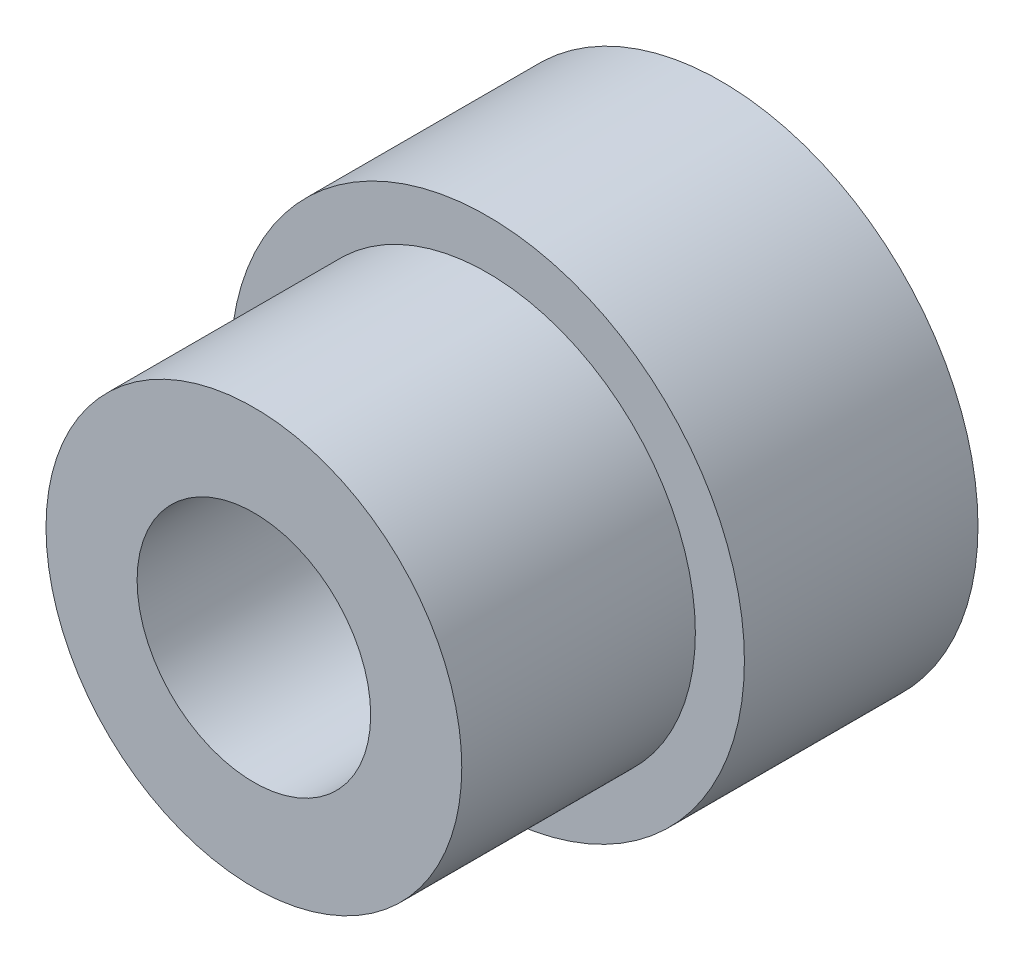
SolidWorks part; units mm, degrees
ref_plane "前视基准面" through (0, 0, 0) normal (0, 0, 1) x (1, 0, 0)
ref_plane "上视基准面" through (0, 0, 0) normal (0, 1, 0) x (1, 0, 0)
ref_plane "右视基准面" through (0, 0, 0) normal (1, 0, 0) x (0, 0, -1)
sketch "草图1" plane through (0, 0, 0) normal (0, 0, 1) x (1, 0, 0)
  circle A0 centre (0, 0) radius 5.5
  dimension "D1" = 11
extrude "凸台-拉伸1" add sketch "草图1" along normal blind 5
sketch "草图2" plane through (0, 0, 5) normal (0, 0, 1) x (1, 0, 0)
  circle A0 centre (0, 0) radius 4.45
  dimension "D1" = 8.9
extrude "凸台-拉伸2" add sketch "草图2" along normal blind 5
sketch "草图3" plane through (0, 0, 10) normal (0, 0, 1) x (1, 0, 0)
  circle A0 centre (0, 0) radius 2.5
  dimension "D1" = 5
extrude "切除-拉伸1" cut sketch "草图3" against normal through all
